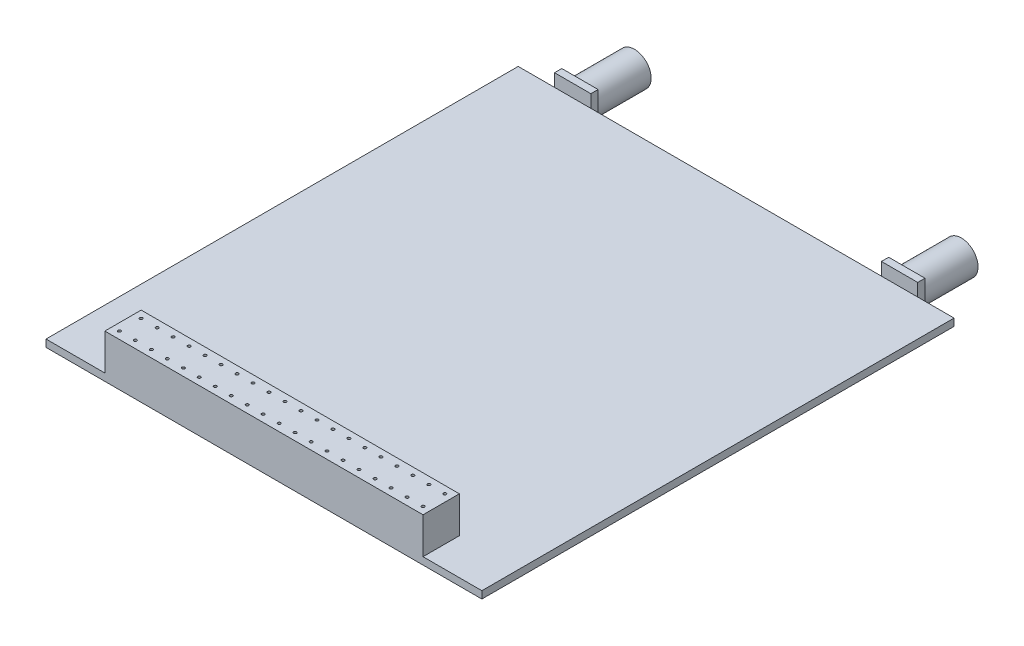
SolidWorks part; units mm, degrees
ref_plane "前视基准面" through (0, 0, 0) normal (0, 0, 1) x (1, 0, 0)
ref_plane "上视基准面" through (0, 0, 0) normal (0, 1, 0) x (1, 0, 0)
ref_plane "右视基准面" through (0, 0, 0) normal (1, 0, 0) x (0, 0, -1)
other "Configuration Table"
sketch "草图1" plane through (0, 0, 0) normal (0, 1, 0) x (1, 0, 0)
  line L1 (-61.9231, 31.7308) -> (-1.9231, 31.7308)
  line L2 (-61.9231, 31.7308) -> (-61.9231, -33.2692)
  line L3 (-61.9231, -33.2692) -> (-1.9231, -33.2692)
  line L4 (-1.9231, 31.7308) -> (-1.9231, -33.2692)
  dimension "D1" = 65
  dimension "D2" = 60
extrude "凸台-拉伸1" add sketch "草图1" along normal blind 1 contours L2 L1 L4 L3
sketch "草图7" plane through (0, 1, 0) normal (0, 1, 0) x (1, 0, 0)
  line L0 (-61.9231, -33.2692) -> (-1.9231, -33.2692) construction
  line L1 (-53.8231, -28.2692) -> (-10.0231, -28.2692)
  line L2 (-53.8231, -28.2692) -> (-53.8231, -33.2692)
  line L3 (-53.8231, -33.2692) -> (-10.0231, -33.2692)
  line L4 (-10.0231, -28.2692) -> (-10.0231, -33.2692)
  line L5 (-61.9231, 31.7308) -> (-61.9231, -33.2692) construction
  dimension "D1" = 43.8
  dimension "D2" = 5
  dimension "D3" = 8.1
extrude "凸台-拉伸3" add sketch "草图7" along normal blind 5 contours L2 L1 L4 L3
sketch "草图8" plane through (0, 6, 0) normal (0, 1, 0) x (1, 0, 0)
  line L0 (-53.8231, -28.2692) -> (-10.0231, -28.2692) construction
  line L1 (-53.8231, -28.2692) -> (-53.8231, -33.2692) construction
  circle A0 centre (-52.8231, -29.2692) radius 0.2
  dimension "D1" = 1
  dimension "D2" = 1
extrude "切除-拉伸2" cut sketch "草图8" against normal blind 5
pattern_linear "阵列(线性)1" count 20 spacing 2.2 along (1, 0, 0) count 2 spacing 3 along (0, 0, 1) of "切除-拉伸2"
sketch "草图9" plane through (0, 0, -31.7308) normal (0, 0, -1) x (-1, 0, 0)
  line L0 (1.9231, 1) -> (1.9231, 0) construction
  line L1 (6.9231, 2.75) -> (11.9231, 2.75)
  line L2 (6.9231, 2.75) -> (6.9231, -2.25)
  line L3 (6.9231, -2.25) -> (11.9231, -2.25)
  line L4 (11.9231, 2.75) -> (11.9231, -2.25)
  line L5 (61.9231, 1) -> (1.9231, 1) construction
  point P6 (1.9231, 0.5)
  dimension "D1" = 5
  dimension "D2" = 5
  dimension "D3" = 5
  dimension "D4" = 1.75
extrude "凸台-拉伸4" add sketch "草图9" along normal blind 1
sketch "草图10" plane through (0, 0, -32.7308) normal (0, 0, -1) x (-1, 0, 0)
  line L0 (6.9231, 2.75) -> (6.9231, -2.25) construction
  line L1 (6.9231, -2.25) -> (11.9231, -2.25) construction
  circle A0 centre (9.4231, 0.25) radius 2.3
  dimension "D1" = 2.5
  dimension "D2" = 2.5
extrude "凸台-拉伸5" add sketch "草图10" along normal blind 7.5
sketch "草图11" plane through (0, 0, -40.2308) normal (0, 0, -1) x (-1, 0, 0)
  line L0 (6.9231, 1) -> (6.9231, 0) construction
  line L1 (11.9231, 2.75) -> (6.9231, 2.75) construction
  circle A0 centre (9.4231, 0.25) radius 2.2
  point P4 (0, 0)
  point P6 (9.3949, 0.4083)
  dimension "D1" = 2.5
  dimension "D2" = 2.5
extrude "切除-拉伸3" cut sketch "草图11" against normal blind 7.5
pattern_linear "阵列(线性)2" count 2 spacing 45 along (-1, 0, 0) of "切除-拉伸3", "凸台-拉伸5", "凸台-拉伸4"
